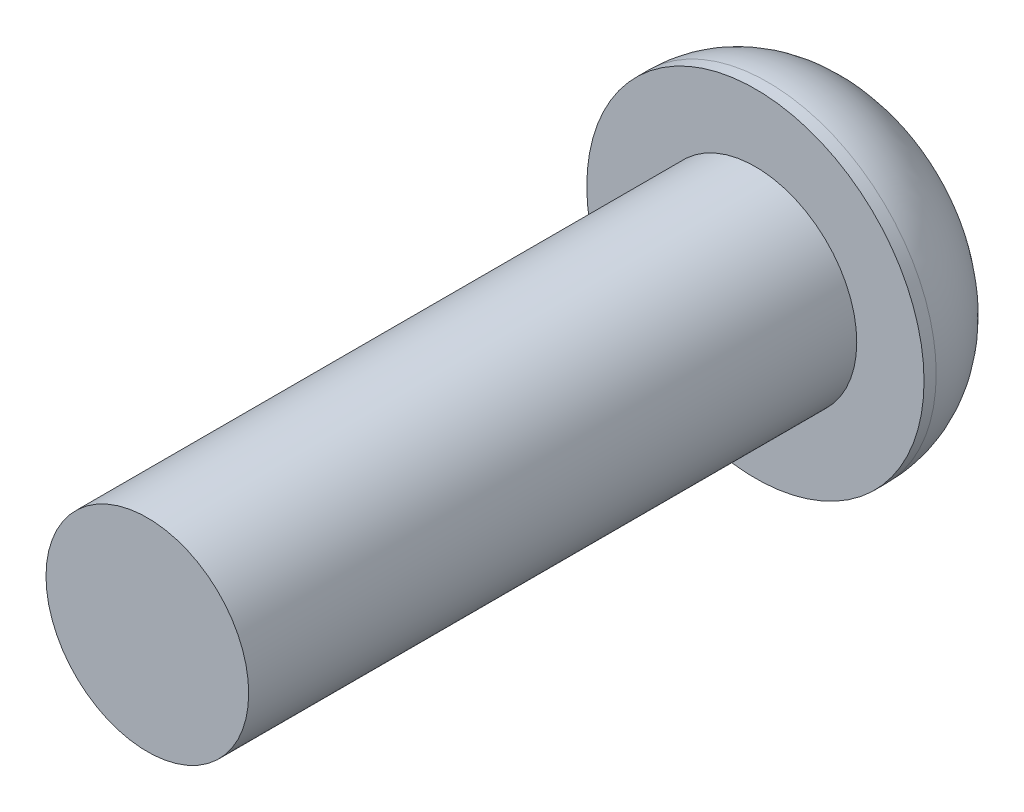
SolidWorks part; units mm, degrees
ref_plane "Front Plane" through (0, 0, 0) normal (0, 0, 1) x (1, 0, 0)
ref_plane "Top Plane" through (0, 0, 0) normal (0, 1, 0) x (1, 0, 0)
ref_plane "Right Plane" through (0, 0, 0) normal (1, 0, 0) x (0, 0, -1)
sketch "Sketch1" plane through (0, 0, 0) normal (0, 0, 1) x (1, 0, 0)
  circle A0 centre (0, 0) radius 2.5
  dimension "D1" = 5
extrude "Boss-Extrude1" add sketch "Sketch1" along normal blind 15
sketch "Sketch2" plane through (0, 0, 0) normal (0, 0, -1) x (-1, 0, 0)
  circle A0 centre (0, 0) radius 4.1596
extrude "Boss-Extrude2" add sketch "Sketch2" along normal blind 2.8
fillet "Fillet1" radius 2.5 1 edges at (-4.1596, 0, -2.8)
sketch "Sketch3" plane through (0, 0, -2.8) normal (0, 0, -1) x (-1, 0, 0)
  line L1 (1.3924, -0.6365) -> (1.2475, 0.8876)
  line L2 (1.2475, 0.8876) -> (-0.145, 1.5241)
  line L3 (-0.145, 1.5241) -> (-1.3924, 0.6365)
  line L4 (-1.3924, 0.6365) -> (-1.2475, -0.8876)
  line L5 (-1.2475, -0.8876) -> (0.145, -1.5241)
  line L6 (0.145, -1.5241) -> (1.3924, -0.6365)
  circle A0 centre (0, 0) radius 1.3259 construction
extrude "Cut-Extrude1" cut sketch "Sketch3" against normal blind 2
